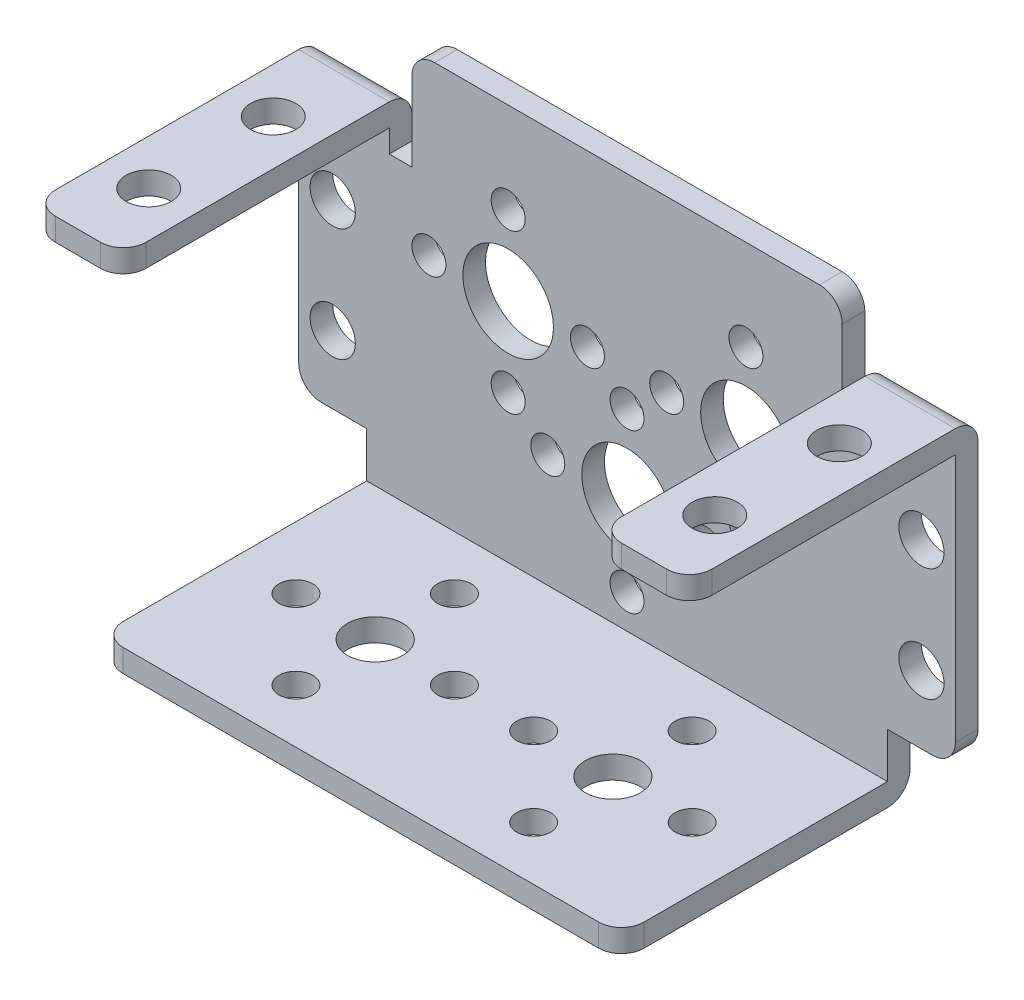
SolidWorks part; units mm, degrees
ref_plane "前视基准面" through (0, 0, 0) normal (0, 0, 1) x (1, 0, 0)
ref_plane "上视基准面" through (0, 0, 0) normal (0, 1, 0) x (1, 0, 0)
ref_plane "右视基准面" through (0, 0, 0) normal (1, 0, 0) x (0, 0, -1)
sketch "草图3" plane through (0, 0, 0) normal (0, 0, 1) x (1, 0, 0)
  line L0 (9.413, 70.4955) -> (172.0083, 70.4955) construction
  line L1 (-30.4275, 21.2979) -> (27.5725, 21.2979)
  line L2 (-30.4275, 21.2979) -> (-30.4275, -15.7021)
  line L3 (-30.4275, -15.7021) -> (27.5725, -15.7021)
  line L4 (27.5725, 21.2979) -> (27.5725, -15.7021)
  dimension "D1" = 58
  dimension "D2" = 37
extrude "凸台-拉伸1" add sketch "草图3" along normal blind 2
sketch "草图4" plane through (0, 0, 2) normal (0, 0, 1) x (1, 0, 0)
  line L0 (27.5725, -15.7021) -> (27.5725, 21.2979) construction
  line L1 (-30.4275, -15.7021) -> (27.5725, -15.7021)
  line L2 (-30.4275, -15.7021) -> (-30.4275, -13.7021)
  line L3 (-30.4275, -13.7021) -> (27.5725, -13.7021)
  line L4 (27.5725, -15.7021) -> (27.5725, -13.7021)
  dimension "D1" = 2
extrude "凸台-拉伸2" add sketch "草图4" along normal blind 23.5
sketch "草图5" plane through (0, 0, 2) normal (0, 0, 1) x (1, 0, 0)
  line L0 (-30.4275, 21.2979) -> (-30.4275, -13.7021) construction
  line L1 (-30.4275, 14.2979) -> (-22.4275, 14.2979)
  line L2 (-30.4275, 14.2979) -> (-30.4275, 16.2979)
  line L3 (-30.4275, 16.2979) -> (-22.4275, 16.2979)
  line L4 (-22.4275, 14.2979) -> (-22.4275, 16.2979)
  line L5 (-30.4275, -15.7021) -> (27.5725, -15.7021) construction
  line L6 (0, 0) -> (0, 20.1135) construction
  dimension "D1" = 2
  dimension "D2" = 32
  dimension "D3" = 8
extrude "凸台-拉伸3" add sketch "草图5" along normal blind 23.5
pattern_linear "阵列(线性)1" count 2 spacing 50 along (1, 0, 0) of "凸台-拉伸3"
sketch "草图6" plane through (0, 0, 2) normal (0, 0, 1) x (1, 0, 0)
  line L2 (-30.4275, -15.7021) -> (-24.4275, -15.7021)
  line L3 (-30.4275, -15.7021) -> (-30.4275, -9.7021)
  line L4 (-30.4275, -9.7021) -> (-24.4275, -9.7021)
  line L5 (-24.4275, -15.7021) -> (-24.4275, -9.7021)
  dimension "D1" = 6
  dimension "D2" = 6
extrude "切除-拉伸1" cut sketch "草图6" against normal through all both and the other way through all
pattern_linear "阵列(线性)2" count 2 spacing 52 along (1, 0, 0) of "切除-拉伸1"
sketch "草图7" plane through (0, 0, 2) normal (0, 0, 1) x (1, 0, 0)
  line L0 (-30.4275, 21.2979) -> (-30.4275, 16.2979)
  line L1 (-30.4275, 16.2979) -> (-22.4275, 16.2979)
  line L2 (-22.4275, 16.2979) -> (-22.4275, 14.2979)
  line L3 (-22.4275, 14.2979) -> (-22.4275, 12.2979)
  line L4 (-22.4275, 12.2979) -> (-20.4275, 12.2979)
  line L5 (-20.4275, 12.2979) -> (-20.4275, 21.2979)
  line L6 (27.5725, 21.2979) -> (-30.4275, 21.2979) construction
  line L7 (-20.4275, 21.2979) -> (-30.4275, 21.2979)
  dimension "D1" = 9
  dimension "D2" = 2
extrude "切除-拉伸2" cut sketch "草图7" against normal blind 23.5
sketch "草图8" plane through (0, 0, 2) normal (0, 0, 1) x (1, 0, 0)
  line L0 (27.5725, 16.2979) -> (27.5725, 21.2979)
  line L1 (27.5725, 21.2979) -> (17.5725, 21.2979)
  line L2 (27.5725, 21.2979) -> (-20.4275, 21.2979) construction
  line L3 (17.5725, 21.2979) -> (17.5725, 12.2979)
  line L4 (17.5725, 12.2979) -> (19.5725, 12.2979)
  line L5 (19.5725, 12.2979) -> (19.5725, 16.2979)
  line L6 (19.5725, 16.2979) -> (27.5725, 16.2979)
  dimension "D1" = 2
  dimension "D2" = 9
extrude "切除-拉伸3" cut sketch "草图8" against normal blind 23.5
sketch "草图9" plane through (0, 0, 2) normal (0, 0, 1) x (1, 0, 0)
  line L0 (-24.4275, -9.7021) -> (-30.4275, -9.7021) construction
  line L3 (-20.4275, 12.2979) -> (-20.4275, 21.2979) construction
  line L4 (-20.4275, 21.2979) -> (17.5725, 21.2979) construction
  line L5 (17.5725, 21.2979) -> (17.5725, 12.2979) construction
  line L6 (17.5725, 21.2979) -> (17.5725, 12.2979) construction
  line L7 (-1.4275, 21.2979) -> (-1.4275, -9.2021) construction
  circle A0 centre (-27.4275, 6.2979) radius 2
  circle A1 centre (-27.4275, -3.7021) radius 2
  circle A2 centre (-11.9275, 6.2979) radius 4
  circle A3 centre (-1.4275, -3.7021) radius 4
  circle A4 centre (-1.4275, 3.2979) radius 1.5
  circle A5 centre (-1.4275, -10.7021) radius 1.5
  circle A6 centre (-11.9275, -0.7021) radius 1.5
  circle A7 centre (-11.9275, 13.2979) radius 1.5
  circle A8 centre (-18.9275, 6.2979) radius 1.5
  circle A9 centre (-4.9275, 6.2979) radius 1.5
  circle A10 centre (-8.4275, -3.7021) radius 1.5
  circle A11 centre (5.5725, -3.7021) radius 1.5
  circle A12 centre (9.0725, 13.2979) radius 1.5
  circle A13 centre (2.0725, 6.2979) radius 1.5
  circle A14 centre (9.0725, -0.7021) radius 1.5
  circle A15 centre (9.0725, 6.2979) radius 4
  circle A16 centre (16.0725, 6.2979) radius 1.5
  circle A17 centre (24.5725, -3.7021) radius 2
  circle A18 centre (24.5725, 6.2979) radius 2
  point P4 (-27.4275, -9.7021)
  dimension "D1" = 4
  dimension "D2" = 4
  dimension "D6" = 8
  dimension "D7" = 8
  dimension "D9" = 3
  dimension "D10" = 3
  dimension "D11" = 7
  dimension "D16" = 7
  dimension "D17" = 0
  dimension "D3" = 16
  dimension "D4" = 10
  dimension "D5" = 10.5
  dimension "D8" = 7
  dimension "D12" = 7
  dimension "D13" = 7
  dimension "D14" = 7
  dimension "D15" = 7
extrude "切除-拉伸4" cut sketch "草图9" against normal blind 23.5
sketch "草图11" plane through (0, -13.7021, 0) normal (0, 1, 0) x (1, 0, 0)
  line L0 (-24.4275, -2) -> (-24.4275, -25.5) construction
  line L1 (-24.4275, -25.5) -> (21.5725, -25.5) construction
  line L2 (-24.4275, 0) -> (-24.4275, -25.5) construction
  line L3 (-24.4275, -13.75) -> (21.5725, -13.75) construction
  line L4 (21.5725, 0) -> (21.5725, -25.5) construction
  line L5 (-1.4275, -25.5) -> (-1.4275, -2) construction
  line L6 (-2.9275, -2) -> (0.0725, -2) construction
  line L7 (-1.4275, -25.5) -> (-24.4275, -25.5) construction
  circle A0 centre (-11.9275, -13.75) radius 2.4471
  circle A1 centre (-18.9275, -13.75) radius 1.5
  circle A2 centre (-11.9275, -20.75) radius 1.5
  circle A3 centre (-4.9275, -13.75) radius 1.5
  circle A4 centre (-11.9275, -6.75) radius 1.5
  circle A5 centre (9.0725, -20.75) radius 1.5
  circle A6 centre (2.0725, -13.75) radius 1.5
  circle A7 centre (9.0725, -6.75) radius 1.5
  circle A8 centre (9.0725, -13.75) radius 2.4471
  circle A9 centre (16.0725, -13.75) radius 1.5
  point P29 (-12.9275, -13.75)
  dimension "D1" = 3
  dimension "D2" = 3
  dimension "D3" = 3
  dimension "D4" = 3
  dimension "D5" = 7
  dimension "D6" = 7
  dimension "D7" = 7
  dimension "D8" = 7
  dimension "D9" = 7
extrude "切除-拉伸5" cut sketch "草图11" against normal through all
fillet "圆角1" radius 2 13 edges at (-1.4275, -15.7021, 0) (-30.4275, -9.7021, 1) (27.5725, -9.7021, 1) (-20.4275, 21.2979, 1) (17.5725, 21.2979, 1) (23.5725, 16.2979, 0) (-26.4275, 16.2979, 0) (27.5725, 15.2979, 25.5) (19.5725, 15.2979, 25.5) (21.5725, -14.7021, 25.5) (-24.4275, -14.7021, 25.5) (-22.4275, 15.2979, 25.5) (-30.4275, 15.2979, 25.5)
sketch "草图12" plane through (0, 16.2979, 0) normal (0, 1, 0) x (1, 0, 0)
  line L1 (-30.4275, -23.5) -> (-30.4275, -2) construction
  line L2 (-22.4275, -23.5) -> (-22.4275, -2) construction
  line L3 (-30.4275, 0) -> (27.5725, 0) construction
  line L4 (27.5725, 0) -> (-1.4275, 0) construction
  line L5 (-1.4275, 0) -> (-1.4275, -26.9172) construction
  line L6 (-1.4275, 0) -> (-1.4275, -2) construction
  line L7 (-11.9275, -13.75) -> (-34.1061, -13.75) construction
  circle A0 centre (-26.4275, -19.25) radius 2
  circle A1 centre (-26.4275, -8.25) radius 2
  circle A2 centre (23.5725, -19.25) radius 2
  circle A3 centre (23.5725, -8.25) radius 2
  dimension "D2" = 4
  dimension "D3" = 4
  dimension "D1" = 5.5
  dimension "D4" = 8
  dimension "D5" = 4
  dimension "D6" = 11
  dimension "D7" = 4
extrude "切除-拉伸6" cut sketch "草图12" against normal blind 23.5
